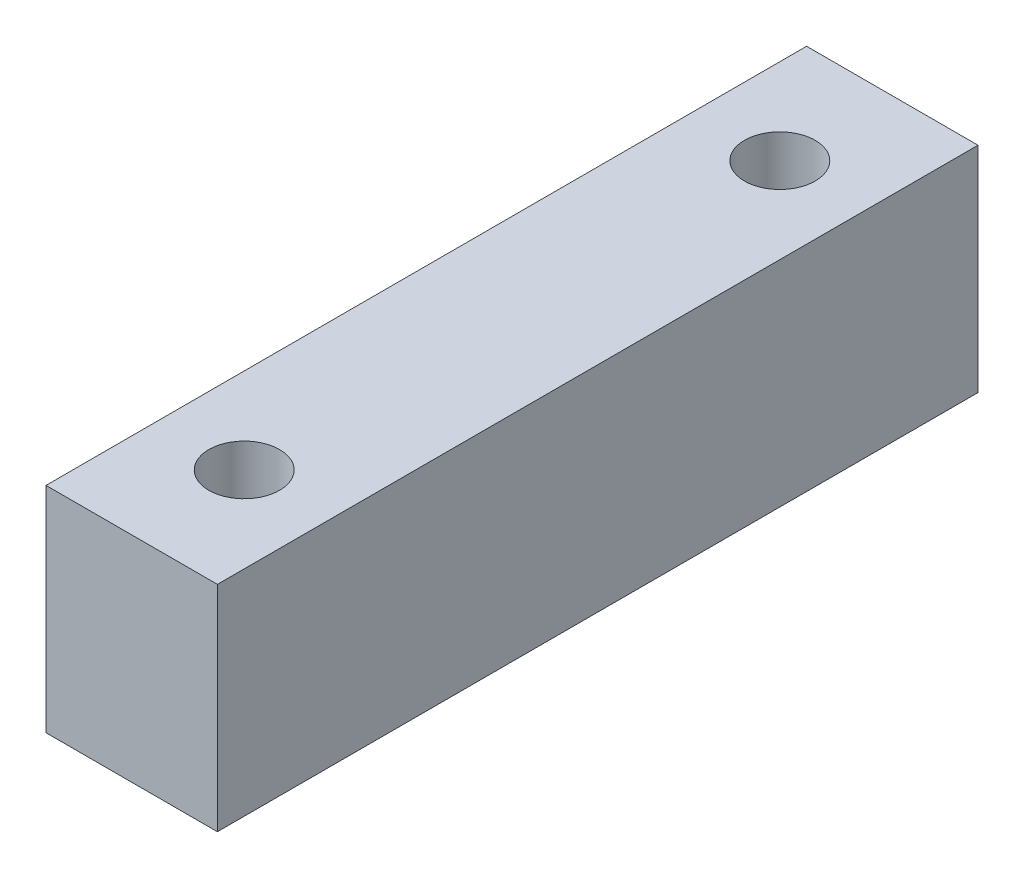
SolidWorks part; units mm, degrees
ref_plane "前视基准面" through (0, 0, 0) normal (0, 0, 1) x (1, 0, 0)
ref_plane "上视基准面" through (0, 0, 0) normal (0, 1, 0) x (1, 0, 0)
ref_plane "右视基准面" through (0, 0, 0) normal (1, 0, 0) x (0, 0, -1)
sketch "草图1" plane through (0, 0, 0) normal (0, 1, 0) x (1, 0, 0)
  line L1 (-4, 17.75) -> (4, 17.75)
  line L2 (-4, 17.75) -> (-4, -17.75)
  line L3 (-4, -17.75) -> (4, -17.75)
  line L4 (4, 17.75) -> (4, -17.75)
  line L5 (-4, 17.75) -> (4, -17.75) construction
  line L6 (-4, -17.75) -> (4, 17.75) construction
  point P0 (0, 0)
  dimension "D1" = 8
  dimension "D2" = 35.5
extrude "凸台-拉伸1" add sketch "草图1" along normal blind 10
sketch "草图2" plane through (0, 10, 0) normal (0, 1, 0) x (1, 0, 0)
  line L0 (0, 12.5) -> (0, -12.5) construction
  circle A0 centre (0, 12.5) radius 1.65
  circle A1 centre (0, -12.5) radius 1.65
  point P4 (0, 0)
  dimension "D1" = 3.3
  dimension "D2" = 25
extrude "切除-拉伸1" cut sketch "草图2" against normal up to next
sketch "草图3" plane through (0, 0, 0) normal (0, 1, 0) x (1, 0, 0)
  circle A0 centre (0, 12.5) radius 3
  circle A1 centre (0, -12.5) radius 3
  dimension "D1" = 6
extrude "切除-拉伸2" cut sketch "草图3" along normal offset from surface (7 mm away) 3 up to face at (0, 10, -10.85)
